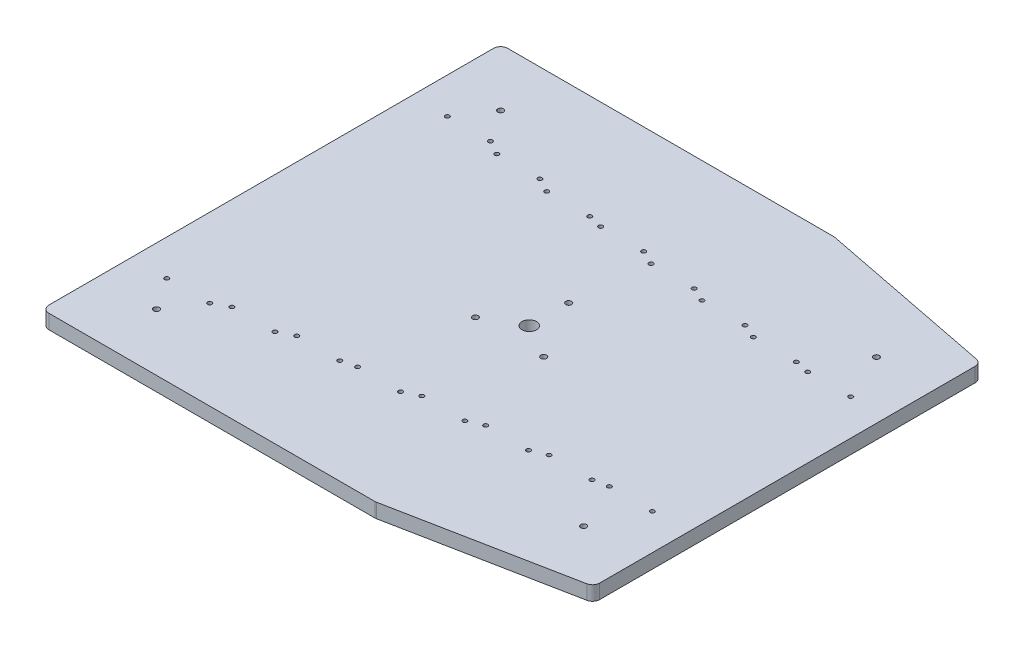
SolidWorks part; units mm, degrees
material "AISI Type 316L stainless steel"
ref_plane "Front Plane" through (0, 0, 0) normal (0, 0, 1) x (1, 0, 0)
ref_plane "Top Plane" through (0, 0, 0) normal (0, 1, 0) x (1, 0, 0)
ref_plane "Right Plane" through (0, 0, 0) normal (1, 0, 0) x (0, 0, -1)
sketch "Sketch1" plane through (0, 0, 0) normal (0, 1, 0) x (1, 0, 0)
  line L1 (-228.6, -203.2) -> (228.6, -203.2)
  line L2 (-228.6, -203.2) -> (-228.6, 203.2)
  line L3 (-228.6, 203.2) -> (228.6, 203.2)
  line L4 (228.6, -203.2) -> (228.6, 203.2)
  line L5 (-228.6, -203.2) -> (228.6, 203.2) construction
  line L6 (-228.6, 203.2) -> (228.6, -203.2) construction
  point P0 (0, 0)
  dimension "D1" = 457.2
  dimension "D2" = 406.4
extrude "Boss-Extrude1" add sketch "Sketch1" along normal blind 12.7
hole_wizard "#6 Clearance Hole1" positions "Sketch2" profile "Sketch3" hole size "#6" standard "ANSI Inch" end condition through all
sketch "Sketch2" plane through (0, 0, 0) normal (0, -1, 0) x (-1, 0, 0)
  line L0 (-228.6, 0) -> (228.6, 0) construction
  line L1 (-228.6, -203.2) -> (-228.6, 203.2) construction
  line L2 (228.6, 203.2) -> (228.6, -203.2) construction
  point P0 (-196.85, 87.8764)
  point P3 (-158.75, 87.8764)
  point P6 (-146.05, 90.4545)
  point P9 (-107.95, 90.4545)
  point P12 (-95.25, 95.8317)
  point P15 (-57.15, 95.8317)
  point P18 (-44.45, 101.5035)
  point P21 (-6.35, 101.5035)
  point P24 (6.35, 107.6173)
  point P27 (44.45, 107.6173)
  point P30 (57.15, 110.711)
  point P33 (95.25, 110.711)
  point P36 (107.95, 117.3404)
  point P39 (146.05, 117.3404)
  point P42 (158.75, 124.2644)
  point P45 (196.85, 124.2644)
  point P56 (196.85, -124.2644)
  point P57 (158.75, -124.2644)
  point P58 (146.05, -117.3404)
  point P59 (107.95, -117.3404)
  point P60 (95.25, -110.711)
  point P61 (57.15, -110.711)
  point P62 (44.45, -107.6173)
  point P63 (6.35, -107.6173)
  point P64 (-6.35, -101.5035)
  point P65 (-44.45, -101.5035)
  point P66 (-57.15, -95.8317)
  point P67 (-95.25, -95.8317)
  point P68 (-107.95, -90.4545)
  point P69 (-146.05, -90.4545)
  point P70 (-158.75, -87.8764)
  point P71 (-196.85, -87.8764)
sketch "Sketch3" plane through (196.85, 0, -87.8764) normal (1, 0, 0) x (0, 0, -1)
  line L0 (0, 0) -> (0, 12.7)
  line L1 (0, 12.7) -> (1.8986, 12.7)
  line L2 (1.8986, 12.7) -> (1.8986, 0)
  line L5 (1.8986, 0) -> (0, 0)
  line L11 (0, -6.35) -> (0, 107.95) construction
  dimension "Thru Hole Dia." = 3.7973
  dimension "Thru Hole Depth" = 12.7
sketch "Sketch4" plane through (0, 12.7, 0) normal (0, 1, 0) x (1, 0, 0)
  line L0 (-196.85, 124.2644) -> (-158.75, 124.2644) construction
  line L1 (-196.85, 130.6144) -> (-158.75, 130.6144)
  line L2 (-196.85, 117.9144) -> (-158.75, 117.9144)
  line L3 (-146.05, 117.3404) -> (-107.95, 117.3404) construction
  line L4 (-146.05, 123.6904) -> (-107.95, 123.6904)
  line L5 (-146.05, 110.9904) -> (-107.95, 110.9904)
  line L6 (-95.25, 110.711) -> (-57.15, 110.711) construction
  line L7 (-95.25, 117.061) -> (-57.15, 117.061)
  line L8 (-95.25, 104.361) -> (-57.15, 104.361)
  line L9 (-44.45, 107.6173) -> (-6.35, 107.6173) construction
  line L10 (-44.45, 113.9673) -> (-6.35, 113.9673)
  line L11 (-44.45, 101.2673) -> (-6.35, 101.2673)
  line L12 (6.35, 101.5035) -> (44.45, 101.5035) construction
  line L13 (6.35, 107.8535) -> (44.45, 107.8535)
  line L14 (6.35, 95.1535) -> (44.45, 95.1535)
  line L15 (57.15, 95.8317) -> (95.25, 95.8317) construction
  line L16 (57.15, 102.1817) -> (95.25, 102.1817)
  line L17 (57.15, 89.4817) -> (95.25, 89.4817)
  line L18 (107.95, 90.4545) -> (146.05, 90.4545) construction
  line L19 (107.95, 96.8045) -> (146.05, 96.8045)
  line L20 (107.95, 84.1045) -> (146.05, 84.1045)
  line L21 (158.75, 87.8764) -> (196.85, 87.8764) construction
  line L22 (158.75, 94.2264) -> (196.85, 94.2264)
  line L23 (158.75, 81.5264) -> (196.85, 81.5264)
  line L24 (-228.6, 0) -> (228.6, 0) construction
  line L25 (-228.6, 203.2) -> (-228.6, -203.2) construction
  line L26 (228.6, -203.2) -> (228.6, 203.2) construction
  line L27 (-196.85, -124.2644) -> (-158.75, -124.2644) construction
  line L28 (-196.85, -130.6144) -> (-158.75, -130.6144)
  line L29 (-196.85, -117.9144) -> (-158.75, -117.9144)
  line L30 (-146.05, -117.3404) -> (-107.95, -117.3404) construction
  line L31 (-146.05, -123.6904) -> (-107.95, -123.6904)
  line L32 (-146.05, -110.9904) -> (-107.95, -110.9904)
  line L33 (-95.25, -110.711) -> (-57.15, -110.711) construction
  line L34 (-95.25, -117.061) -> (-57.15, -117.061)
  line L35 (-95.25, -104.361) -> (-57.15, -104.361)
  line L36 (-44.45, -107.6173) -> (-6.35, -107.6173) construction
  line L37 (-44.45, -113.9673) -> (-6.35, -113.9673)
  line L38 (-44.45, -101.2673) -> (-6.35, -101.2673)
  line L39 (6.35, -101.5035) -> (44.45, -101.5035) construction
  line L40 (6.35, -107.8535) -> (44.45, -107.8535)
  line L41 (6.35, -95.1535) -> (44.45, -95.1535)
  line L42 (57.15, -95.8317) -> (95.25, -95.8317) construction
  line L43 (57.15, -102.1817) -> (95.25, -102.1817)
  line L44 (57.15, -89.4817) -> (95.25, -89.4817)
  line L45 (107.95, -90.4545) -> (146.05, -90.4545) construction
  line L46 (107.95, -96.8045) -> (146.05, -96.8045)
  line L47 (107.95, -84.1045) -> (146.05, -84.1045)
  line L48 (158.75, -87.8764) -> (196.85, -87.8764) construction
  line L49 (158.75, -94.2264) -> (196.85, -94.2264)
  line L50 (158.75, -81.5264) -> (196.85, -81.5264)
  arc A0 (-196.85, 130.6144) -> (-196.85, 117.9144) centre (-196.85, 124.2644) ccw
  arc A1 (-158.75, 117.9144) -> (-158.75, 130.6144) centre (-158.75, 124.2644) ccw
  arc A2 (-146.05, 123.6904) -> (-146.05, 110.9904) centre (-146.05, 117.3404) ccw
  arc A3 (-107.95, 110.9904) -> (-107.95, 123.6904) centre (-107.95, 117.3404) ccw
  arc A6 (-95.25, 117.061) -> (-95.25, 104.361) centre (-95.25, 110.711) ccw
  arc A7 (-57.15, 104.361) -> (-57.15, 117.061) centre (-57.15, 110.711) ccw
  arc A8 (-44.45, 113.9673) -> (-44.45, 101.2673) centre (-44.45, 107.6173) ccw
  arc A9 (-6.35, 101.2673) -> (-6.35, 113.9673) centre (-6.35, 107.6173) ccw
  arc A10 (6.35, 107.8535) -> (6.35, 95.1535) centre (6.35, 101.5035) ccw
  arc A11 (44.45, 95.1535) -> (44.45, 107.8535) centre (44.45, 101.5035) ccw
  arc A12 (57.15, 102.1817) -> (57.15, 89.4817) centre (57.15, 95.8317) ccw
  arc A13 (95.25, 89.4817) -> (95.25, 102.1817) centre (95.25, 95.8317) ccw
  arc A14 (107.95, 96.8045) -> (107.95, 84.1045) centre (107.95, 90.4545) ccw
  arc A15 (146.05, 84.1045) -> (146.05, 96.8045) centre (146.05, 90.4545) ccw
  arc A16 (158.75, 94.2264) -> (158.75, 81.5264) centre (158.75, 87.8764) ccw
  arc A17 (196.85, 81.5264) -> (196.85, 94.2264) centre (196.85, 87.8764) ccw
  circle A22 centre (196.85, 87.8764) radius 1.8987 construction
  arc A27 (-196.85, -130.6144) -> (-196.85, -117.9144) centre (-196.85, -124.2644) cw
  arc A28 (-158.75, -117.9144) -> (-158.75, -130.6144) centre (-158.75, -124.2644) cw
  arc A29 (-146.05, -123.6904) -> (-146.05, -110.9904) centre (-146.05, -117.3404) cw
  arc A30 (-107.95, -110.9904) -> (-107.95, -123.6904) centre (-107.95, -117.3404) cw
  arc A31 (-95.25, -117.061) -> (-95.25, -104.361) centre (-95.25, -110.711) cw
  arc A32 (-57.15, -104.361) -> (-57.15, -117.061) centre (-57.15, -110.711) cw
  arc A33 (-44.45, -113.9673) -> (-44.45, -101.2673) centre (-44.45, -107.6173) cw
  arc A34 (-6.35, -101.2673) -> (-6.35, -113.9673) centre (-6.35, -107.6173) cw
  arc A35 (6.35, -107.8535) -> (6.35, -95.1535) centre (6.35, -101.5035) cw
  arc A36 (44.45, -95.1535) -> (44.45, -107.8535) centre (44.45, -101.5035) cw
  arc A37 (57.15, -102.1817) -> (57.15, -89.4817) centre (57.15, -95.8317) cw
  arc A38 (95.25, -89.4817) -> (95.25, -102.1817) centre (95.25, -95.8317) cw
  arc A39 (107.95, -96.8045) -> (107.95, -84.1045) centre (107.95, -90.4545) cw
  arc A40 (146.05, -84.1045) -> (146.05, -96.8045) centre (146.05, -90.4545) cw
  arc A41 (158.75, -94.2264) -> (158.75, -81.5264) centre (158.75, -87.8764) cw
  arc A42 (196.85, -81.5264) -> (196.85, -94.2264) centre (196.85, -87.8764) cw
  point P4 (-177.8, 124.2644)
  point P16 (-127, 117.3404)
  point P27 (-76.2, 110.711)
  point P32 (-25.4, 107.6173)
  point P41 (25.4, 101.5035)
  point P50 (76.2, 95.8317)
  point P59 (127, 90.4545)
  point P68 (177.8, 87.8764)
  point P96 (-177.8, -124.2644)
  point P103 (-127, -117.3404)
  point P110 (-76.2, -110.711)
  point P117 (-25.4, -107.6173)
  point P124 (25.4, -101.5035)
  point P131 (76.2, -95.8317)
  point P138 (127, -90.4545)
  point P145 (177.8, -87.8764)
extrude "Cut-Extrude1" [suppressed] cut sketch "Sketch4" against normal blind 3.175
sketch "Sketch5" plane through (0, 0, 0) normal (0, -1, 0) x (1, 0, 0)
  line L0 (-228.6, -203.2) -> (228.6, 203.2) construction
  circle A0 centre (0, 0) radius 6.4135
  dimension "D1" = 12.827
extrude "Cut-Extrude2" cut sketch "Sketch5" against normal through all
sketch "Sketch6" plane through (0, 0, 0) normal (0, -1, 0) x (1, 0, 0)
  line L0 (-228.6, -203.2) -> (-228.6, 203.2) construction
  line L1 (-192.913, -121.9914) -> (-196.85, -119.7184)
  line L2 (-196.85, -119.7184) -> (-200.787, -121.9914)
  line L3 (-200.787, -121.9914) -> (-200.787, -126.5374)
  line L4 (-200.787, -126.5374) -> (-196.85, -128.8105)
  line L5 (-196.85, -128.8105) -> (-192.913, -126.5374)
  line L6 (-192.913, -126.5374) -> (-192.913, -121.9914)
  circle A0 centre (-196.85, -124.2644) radius 3.937 construction
  dimension "D1" = 7.874
extrude "Cut-Extrude3" cut sketch "Sketch6" against normal blind 3.175
pattern_sketch "Sketch-Pattern1" of "Cut-Extrude3" driven by "Sketch2"
hole_wizard "#10 Clearance Hole1" positions "Sketch7" profile "Sketch9" hole size "#10" standard "ANSI Inch" end condition through all
sketch "Sketch7" plane through (0, 12.7, 0) normal (0, 1, 0) x (1, 0, 0)
  line L0 (0, 0) -> (0, 34.925) construction
  line L5 (0, 0) -> (30.2459, -17.4625) construction
  line L6 (0, 0) -> (-30.2459, -17.4625) construction
  circle A0 centre (0, 0) radius 34.925 construction
  point P8 (0, 34.925)
  point P28 (30.2459, -17.4625)
  point P29 (-30.2459, -17.4625)
  dimension "D1" = 69.85
sketch "Sketch9" plane through (-30.2459, 12.7, 17.4625) normal (1, 0, 0) x (0, 0, 1)
  line L0 (0, 0) -> (0, 12.7)
  line L1 (0, 12.7) -> (2.5527, 12.7)
  line L2 (2.5527, 12.7) -> (2.5527, 0)
  line L5 (2.5527, 0) -> (0, 0)
  line L11 (0, -6.35) -> (0, 107.95) construction
  dimension "Thru Hole Dia." = 5.1054
  dimension "Thru Hole Depth" = 12.7
sketch "Sketch10" plane through (0, 12.7, 0) normal (0, 1, 0) x (1, 0, 0)
  line L0 (67.0352, -203.2) -> (228.6, -171.45)
  line L1 (-228.6, -203.2) -> (228.6, -203.2) construction
  line L2 (228.6, -203.2) -> (228.6, 203.2) construction
  line L3 (228.6, -171.45) -> (228.6, -203.2)
  line L4 (228.6, -203.2) -> (67.0352, -203.2)
  line L5 (228.6, 0) -> (-228.6, 0) construction
  line L6 (-228.6, 203.2) -> (-228.6, -203.2) construction
  line L7 (228.6, 203.2) -> (67.0352, 203.2)
  line L8 (228.6, 171.45) -> (228.6, 203.2)
  line L9 (67.0352, 203.2) -> (228.6, 171.45)
  circle A0 centre (196.85, 87.8764) radius 1.8987 construction
  dimension "D1" = 31.75
extrude "Cut-Extrude4" cut sketch "Sketch10" against normal through all
fillet "Fillet1" radius 6.35 6 edges at (-228.6, 6.35, 203.2) (-228.6, 6.35, -203.2) (228.6, 6.35, -171.45) (228.6, 6.35, 171.45) (67.0352, 6.35, -203.2) (67.0352, 6.35, 203.2)
hole_wizard "#10 Clearance Hole2" positions "Sketch11" profile "Sketch12" hole size "#10" standard "ANSI Inch" end condition through all
sketch "Sketch11" plane through (0, 12.7, 0) normal (0, 1, 0) x (1, 0, 0)
  line L9 (-222.25, -203.2) -> (66.4172, -203.2) construction
  line L11 (-228.6, 196.85) -> (-228.6, -196.85) construction
  line L12 (228.6, -166.2264) -> (228.6, 166.2264) construction
  line L14 (223.4745, -172.4572) -> (67.6417, -203.0808) construction
  line L16 (228.6, 0) -> (-228.6, 0) construction
  point P39 (177.8, -129.6614)
  point P41 (-177.8, -152.4)
  point P67 (-177.8, 152.4)
  point P68 (177.8, 129.6614)
  dimension "D1" = 50.8
  dimension "D2" = 50.8
  dimension "D3" = 50.8
  dimension "D4" = 50.8
sketch "Sketch12" plane through (177.8, 12.7, 129.6614) normal (1, 0, 0) x (0, 0, 1)
  line L0 (0, 0) -> (0, 12.7)
  line L1 (0, 12.7) -> (2.5527, 12.7)
  line L2 (2.5527, 12.7) -> (2.5527, 0)
  line L5 (2.5527, 0) -> (0, 0)
  line L11 (0, -6.35) -> (0, 107.95) construction
  dimension "Thru Hole Dia." = 5.1054
  dimension "Thru Hole Depth" = 12.7
sketch "Sketch18" plane through (0, 0, 0) normal (0, -1, 0) x (1, 0, 0)
  circle A0 centre (-196.85, -124.2644) radius 6.985
  dimension "D1" = 13.97
extrude "Cut-Extrude6" cut sketch "Sketch18" against normal blind 4.7625
pattern_sketch "Sketch-Pattern2" of "Cut-Extrude6" driven by "Sketch2"
